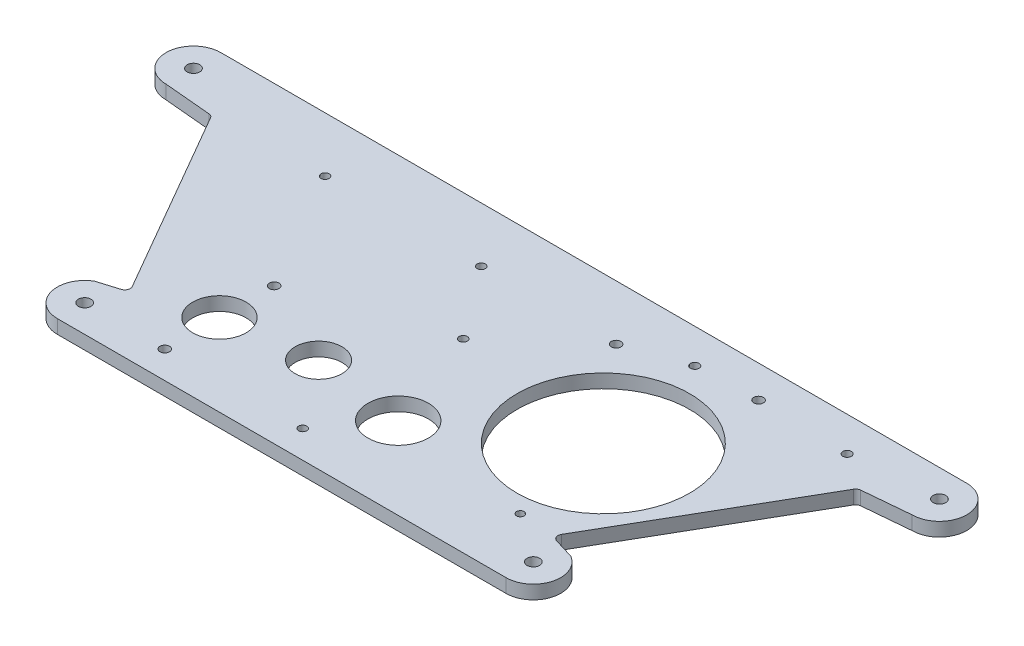
SolidWorks part; units mm, degrees
ref_plane "Front Plane" through (0, 0, 0) normal (0, 0, 1) x (1, 0, 0)
ref_plane "Top Plane" through (0, 0, 0) normal (0, 1, 0) x (1, 0, 0)
ref_plane "Right Plane" through (0, 0, 0) normal (1, 0, 0) x (0, 0, -1)
sketch "Sketch1" plane through (0, 0, 0) normal (0, 1, 0) x (1, 0, 0)
  line L0 (-66.9862, -34.364) -> (-26.7651, -28.5444) construction
  line L1 (-195.1824, -72.464) -> (195.1824, -72.464)
  line L2 (-195.1824, -72.464) -> (-195.1824, 72.464)
  line L3 (-185.8854, 59.764) -> (185.8854, 59.764)
  line L4 (195.1824, -72.464) -> (195.1824, 72.464)
  line L5 (-195.1824, -72.464) -> (195.1824, 72.464) construction
  line L6 (-195.1824, 72.464) -> (195.1824, -72.464) construction
  line L7 (-26.7651, -28.5444) -> (16.021, -34.364) construction
  line L8 (16.021, -34.364) -> (-66.9862, -34.364) construction
  line L9 (16.021, -34.364) -> (72.7907, 4.1122) construction
  line L10 (72.7907, 4.1122) -> (-26.7651, -28.5444) construction
  line L11 (-165.853, 72.464) -> (-82.1789, -72.464)
  line L12 (158.5207, 72.464) -> (74.8465, -72.464)
  line L13 (-195.1824, 72.464) -> (-180.5177, 72.464)
  line L14 (82.1789, -72.464) -> (165.853, 72.464)
  line L15 (-180.5177, 72.464) -> (-96.8436, -72.464) construction
  line L16 (-195.1824, 72.464) -> (-111.5083, -72.464)
  line L17 (96.8436, -72.464) -> (180.5177, 72.464) construction
  line L18 (111.5083, -72.464) -> (195.1824, 72.464)
  line L19 (-173.1854, 47.064) -> (-149.978, 44.9677)
  line L20 (-110.5259, -48.7654) -> (-98.0539, -44.9677)
  line L21 (0, 72.464) -> (0, -72.464) construction
  line L22 (173.1854, 47.064) -> (149.978, 44.9677)
  line L23 (110.5259, -48.7654) -> (98.0539, -44.9677)
  line L24 (72.7907, 4.1122) -> (35.8575, 46.9752) construction
  line L25 (35.8575, 46.9752) -> (91.4446, 57.5288) construction
  line L26 (91.4446, 57.5288) -> (72.7907, 4.1122) construction
  line L27 (72.7907, 4.1122) -> (81.8184, -43.4384) construction
  line L28 (-173.1854, 72.464) -> (195.1824, 72.464)
  line L29 (62.8415, 56.5161) -> (72.7907, 4.1122) construction
  line L30 (72.7907, 4.1122) -> (133.6084, 56.5161) construction
  circle A0 centre (-66.9862, -34.364) radius 12.3825
  circle A1 centre (-66.9862, -34.364) radius 32.2072
  circle A2 centre (-66.9862, -8.964) radius 2.2352
  circle A3 centre (-66.9862, -59.764) radius 2.2352
  circle A4 centre (16.021, -34.364) radius 14.0335
  circle A5 centre (-26.7651, -28.5444) radius 10.8585
  circle A6 centre (72.7907, 4.1122) radius 40.0685
  circle A7 centre (-173.1854, 59.764) radius 2.921
  circle A8 centre (-104.1759, -59.764) radius 2.921
  circle A9 centre (-173.1854, 59.764) radius 12.7
  circle A10 centre (-104.1759, -59.764) radius 12.7
  circle A11 centre (104.1759, -59.764) radius 2.921
  circle A12 centre (104.1759, -59.764) radius 12.7
  circle A13 centre (173.1854, 59.764) radius 2.921
  circle A14 centre (173.1854, 59.764) radius 12.7
  circle A15 centre (35.8575, 46.9752) radius 2.2352
  circle A16 centre (91.4446, 57.5288) radius 2.2352
  circle A17 centre (81.8184, -43.4384) radius 1.7653
  circle A18 centre (62.8415, 56.5161) radius 1.9939
  circle A19 centre (133.6084, 56.5161) radius 1.9939
  point P0 (0, 0)
  point P16 (-72.4812, -34.364)
  dimension "D1" = 64.4144
  dimension "D2" = 24.765
  dimension "D3" = 4.4704
  dimension "D4" = 25.4
  dimension "D6" = 12.7
  dimension "D11" = 28.067
  dimension "D14" = 21.717
  dimension "D15" = 80.137
  dimension "D17" = 50.8
  dimension "D25" = 5.842
  dimension "D26" = 5.842
  dimension "D27" = 12.7
  dimension "D28" = 25.4
  dimension "D30" = 25.4
  dimension "D36" = 4.4704
  dimension "D37" = 4.4704
  dimension "D38" = 3.5306
  dimension "D46" = 3.9878
  dimension "D47" = 53.34
  dimension "D48" = 3.9878
  dimension "D7" = 25.4
  dimension "D8" = 40.64
  dimension "D9" = 43.18
  dimension "D10" = 83.0072
  dimension "D12" = 68.58
  dimension "D13" = 104.775
  dimension "D16" = 120
  dimension "D18" = 120
  dimension "D19" = 12.7
  dimension "D20" = 6.35
  dimension "D21" = 12.7
  dimension "D22" = 12.7
  dimension "D23" = 12.7
  dimension "D24" = 12.7
  dimension "D29" = 31.75
  dimension "D31" = 31.75
  dimension "D32" = 56.58
  dimension "D33" = 48.4
  dimension "D34" = 150
  dimension "D35" = 10.75
  dimension "D39" = 390.3649
  dimension "D40" = 371.7708
  dimension "D41" = 144.9279
  dimension "D42" = 106.8279
  dimension "D43" = 23.3018
  dimension "D44" = 125.161
  dimension "D45" = 60
  dimension "D5" = 2
extrude "Boss-Extrude1" add sketch "Sketch1" along normal blind 6.35 contours L3 A16 L11 A1 A5 L1 L12 A6 A17 A15 A4 | A9 L19 L11 L3 | A9 L3 A7 | L3 A9 A7 | A9 L11 L28 | A9 L3 L11 | L28 L11 L3 L12 | A14 L3 A13 | L22 A14 L3 L14 | L1 L14 L3 L12 | L28 L12 L3 L14 | L3 A14 L14 | L14 A14 L28 | A14 L3 A13 | A12 L23 A11 | L14 A12 L23 | L1 A12 L14 | A5 A1 A3 A2 A0 | A10 L20 A8 | A10 L1 L11 | A10 L11 L20
sketch "Sketch2" plane through (0, 6.35, 0) normal (0, 1, 0) x (1, 0, 0)
  line L0 (-149.978, 44.9677) -> (-98.0539, -44.9677)
  line L1 (-158.5207, 72.464) -> (-74.8465, -72.464)
  line L2 (-173.1854, 72.464) -> (173.1854, 72.464) construction
  line L3 (-104.1759, -72.464) -> (104.1759, -72.464) construction
  line L4 (-154.8545, 66.114) -> (154.8545, 66.114)
  line L5 (-78.5127, -66.114) -> (78.5127, -66.114)
  line L6 (149.978, 44.9677) -> (98.0539, -44.9677)
  line L7 (158.5207, 72.464) -> (74.8465, -72.464)
  line L8 (-26.7651, -28.5444) -> (-26.7651, 66.114) construction
  line L9 (-26.7651, -28.5444) -> (16.021, -34.364) construction
  line L10 (16.021, -34.364) -> (72.7907, 4.1122) construction
  line L11 (35.8575, 46.9752) -> (35.8575, 66.114) construction
  line L12 (16.021, -34.364) -> (16.021, -66.114) construction
  line L13 (-66.9862, -8.964) -> (-110.3325, 66.114) construction
  line L14 (-143.8048, 46.9752) -> (35.8575, 46.9752) construction
  line L15 (-26.7651, -28.5444) -> (-3.029, -59.6709) construction
  line L16 (-145.6379, 50.1502) -> (23.5608, 50.1502)
  line L17 (-141.9717, 43.8002) -> (23.5608, 43.8002)
  line L18 (-113.9987, 66.114) -> (-77.4184, 2.7551)
  line L19 (-106.6663, 66.114) -> (-70.8068, 4.0035)
  line L20 (-29.9401, 66.114) -> (-29.9401, -11.36)
  line L21 (-23.5901, 66.114) -> (-23.5901, -11.36)
  line L22 (-18.8696, -44.1342) -> (-13.0102, -51.8181)
  line L23 (-7.9608, -47.9676) -> (-13.8202, -40.2838)
  line L24 (-9.3096, -27.7144) -> (-3.7696, -28.4679)
  line L25 (-10.1654, -34.0064) -> (-4.6254, -34.76)
  line L26 (12.846, -54.7686) -> (12.846, -66.114)
  line L27 (19.196, -54.7686) -> (19.196, -66.114)
  line L28 (31.1304, -20.2879) -> (32.4639, -19.3841)
  line L29 (34.693, -25.5443) -> (36.0265, -24.6405)
  line L30 (32.6825, 59.272) -> (32.6825, 66.114)
  line L31 (39.0325, 59.272) -> (39.0325, 66.114)
  line L32 (36.6712, 66.114) -> (36.6712, -72.464) construction
  line L33 (30.3212, 66.114) -> (30.3212, -72.464) construction
  line L34 (30.3212, -19.4665) -> (-23.5901, 66.114) construction
  line L35 (18.5434, -13.8684) -> (-31.8413, 66.114) construction
  line L36 (-17.7848, 43.8002) -> (18.5434, -13.8684)
  line L37 (0.3793, 14.9659) -> (-23.5901, -0.1336) construction
  line L38 (-1.7728, 13.6102) -> (-1.7728, 66.114) construction
  line L39 (-1.7728, 13.6102) -> (-26.7651, -28.5444) construction
  line L40 (-1.7728, 13.6102) -> (16.021, -34.364) construction
  line L41 (-4.9478, 66.114) -> (-4.9478, 22.5904)
  line L42 (1.4022, 66.114) -> (1.4022, 22.5904)
  line L43 (-9.0837, 7.5047) -> (-20.7325, -12.1435)
  line L44 (-3.6215, 4.2663) -> (-15.2703, -15.3818)
  line L45 (-1.6267, 4.0863) -> (5.9483, -16.337)
  line L46 (4.3269, 6.2945) -> (11.902, -14.1287)
  circle A0 centre (-66.9862, -34.364) radius 38.5572
  circle A1 centre (72.7907, 4.1122) radius 46.6725
  circle A2 centre (-26.7651, -28.5444) radius 17.4752
  circle A3 centre (16.021, -34.364) radius 20.6502
  circle A4 centre (35.8575, 46.9752) radius 12.7
  circle A5 centre (91.4446, 57.5288) radius 12.7
  circle A6 centre (81.8184, -43.4384) radius 12.7
  circle A7 centre (-99.2828, 46.9752) radius 1.8987
  circle A8 centre (-26.7651, 46.9752) radius 1.8986
  circle A9 centre (-99.2828, 46.9752) radius 9.525
  circle A10 centre (-26.7651, 46.9752) radius 9.525
  circle A11 centre (-3.029, -59.6709) radius 12.7
  circle A12 centre (-3.029, -59.6709) radius 1.8987
  circle A13 centre (-1.7728, 13.6102) radius 9.525
  circle A14 centre (-1.7728, 13.6102) radius 1.8986
  point P96 (-17.7848, 43.8002)
  dimension "D1" = 77.1144
  dimension "D4" = 93.345
  dimension "D7" = 34.9504
  dimension "D8" = 41.3004
  dimension "D9" = 25.4
  dimension "D10" = 25.4
  dimension "D11" = 25.4
  dimension "D12" = 3.7973
  dimension "D13" = 3.7973
  dimension "D14" = 19.05
  dimension "D15" = 19.05
  dimension "D17" = 25.4
  dimension "D18" = 3.7973
  dimension "D28" = 75.5196
  dimension "D31" = 19.05
  dimension "D35" = 3.7973
  dimension "D2" = 6.35
  dimension "D3" = 6.35
  dimension "D5" = 6.35
  dimension "D6" = 6.35
  dimension "D16" = 19.05
  dimension "D19" = 12.793
  dimension "D20" = 6.35
  dimension "D21" = 6.35
  dimension "D22" = 6.35
  dimension "D23" = 6.35
  dimension "D24" = 6.35
  dimension "D25" = 6.35
  dimension "D26" = 6.35
  dimension "D27" = 6.35
  dimension "D29" = 2.0076
  dimension "D30" = 6.35
  dimension "D32" = 6.35
  dimension "D33" = 6.35
  dimension "D34" = 6.35
extrude "Cut-Extrude1" cut sketch "Sketch2" against normal through all contours A7 | A8 | A12 | A14
fillet "Fillet1" radius 2.54 4 edges at (-149.978, 3.175, -44.9677) (-98.0539, 3.175, 44.9677) (149.978, 3.175, -44.9677) (98.0539, 3.175, 44.9677)
